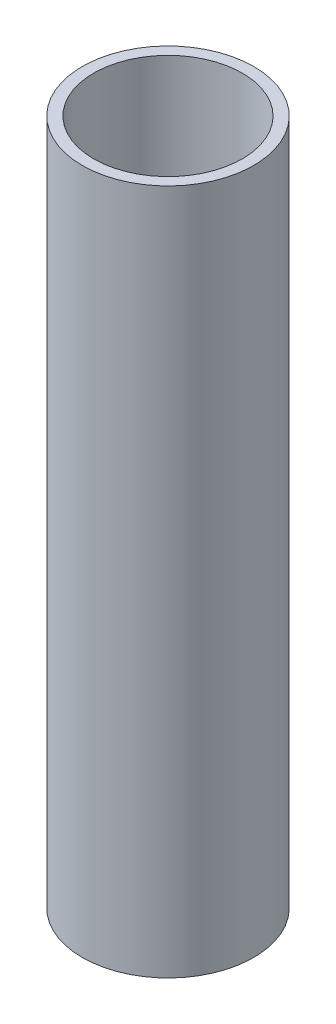
SolidWorks part; units mm, degrees
ref_plane "Front Plane" through (0, 0, 0) normal (0, 0, 1) x (1, 0, 0)
ref_plane "Top Plane" through (0, 0, 0) normal (0, 1, 0) x (1, 0, 0)
ref_plane "Right Plane" through (0, 0, 0) normal (1, 0, 0) x (0, 0, -1)
sketch "Sketch1" plane through (0, 0, 0) normal (0, 1, 0) x (1, 0, 0)
  circle A0 centre (0, 0) radius 19.05
  dimension "D1" = 38.1
extrude "Extrude-Thin1" add sketch "Sketch1" against normal blind 152.4 thin thin type one direction reverse wall 2.54
